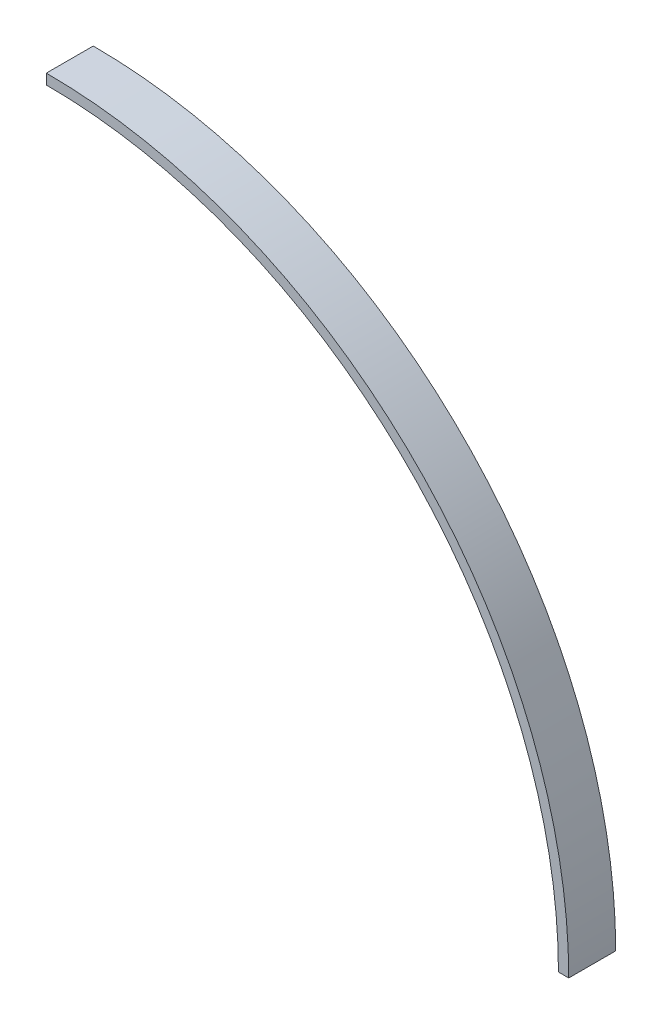
SolidWorks part; units mm, degrees
ref_plane "Front Plane" through (0, 0, 0) normal (0, 0, 1) x (1, 0, 0)
ref_plane "Top Plane" through (0, 0, 0) normal (0, 1, 0) x (1, 0, 0)
ref_plane "Right Plane" through (0, 0, 0) normal (1, 0, 0) x (0, 0, -1)
sketch "Sketch1" plane through (0, 0, 0) normal (0, 0, 1) x (1, 0, 0)
  circle A0 centre (0, 0) radius 252.5
  circle A1 centre (0, 0) radius 248.75
  dimension "D1" = 505
  dimension "D2" = 497.5
extrude "Boss-Extrude1" add sketch "Sketch1" along normal up to surface (21.8 mm away)
sketch "Sketch2" plane through (0, 0, 0) normal (0, 0, -1) x (-1, 0, 0)
  circle A0 centre (0, 0) radius 250.5
  circle A2 centre (0, 0) radius 253.75
  dimension "D1" = 501
  dimension "D2" = 507.5
extrude "Boss-Extrude2" add sketch "Sketch2" along normal blind 1 and the other way up to surface other way up to face at (248.75, 0, 21.8)
other "SurfaceCut1"
other "SurfaceCut2"
